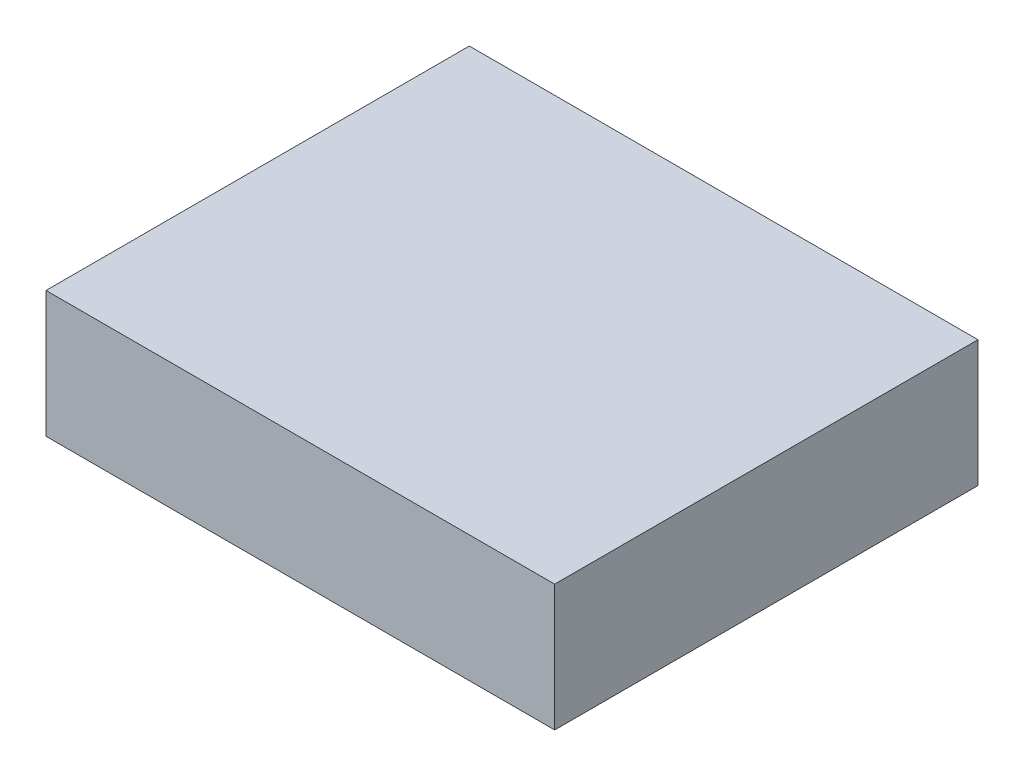
SolidWorks part; units mm, degrees
ref_plane "Front Plane" through (0, 0, 0) normal (0, 0, 1) x (1, 0, 0)
ref_plane "Top Plane" through (0, 0, 0) normal (0, 1, 0) x (1, 0, 0)
ref_plane "Right Plane" through (0, 0, 0) normal (1, 0, 0) x (0, 0, -1)
sketch "Sketch1" plane through (0, 0, 0) normal (0, 1, 0) x (1, 0, 0)
  line L1 (0, 0) -> (74.5, 0)
  line L2 (0, 0) -> (0, -62)
  line L3 (0, -62) -> (74.5, -62)
  line L4 (74.5, 0) -> (74.5, -62)
  dimension "D1" = 74.5
  dimension "D2" = 62
extrude "Boss-Extrude1" add sketch "Sketch1" along normal blind 18.5
